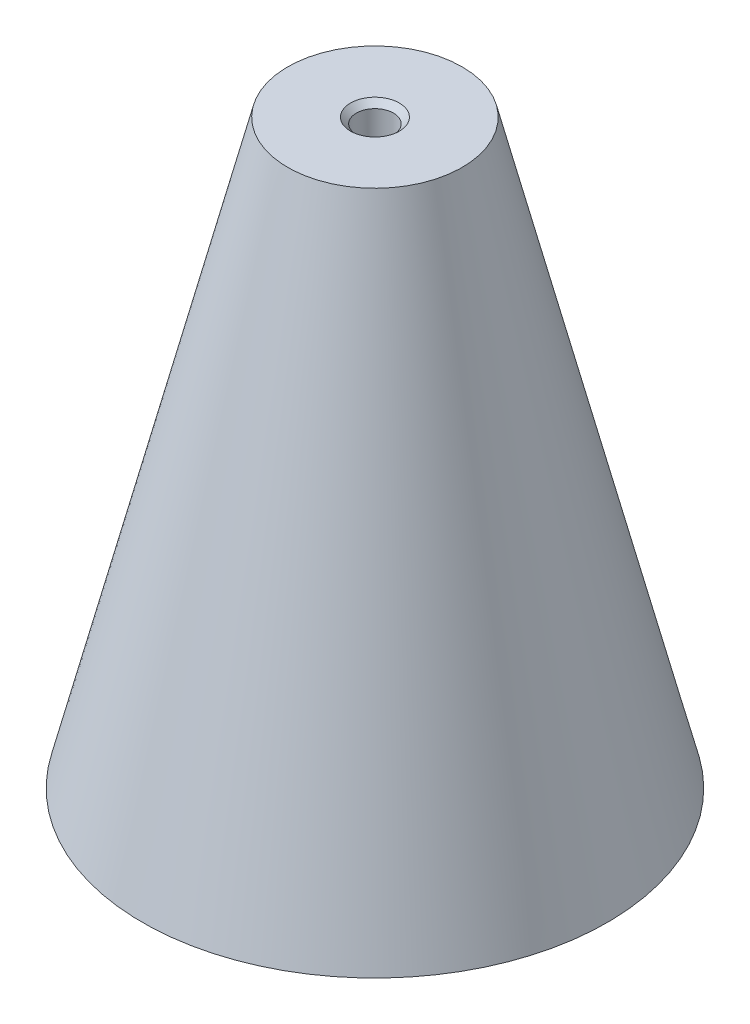
SolidWorks part; units mm, degrees
ref_plane "前视基准面" through (0, 0, 0) normal (0, 0, 1) x (1, 0, 0)
ref_plane "上视基准面" through (0, 0, 0) normal (0, 1, 0) x (1, 0, 0)
ref_plane "右视基准面" through (0, 0, 0) normal (1, 0, 0) x (0, 0, -1)
other "Configuration Table"
sketch "草图3" plane through (0, 0, 0) normal (1, 0, 0) x (0, 0, -1)
  line L0 (-7.5, 0) -> (0, 0)
  line L1 (0, 0) -> (0, -4)
  line L2 (0, -4) -> (-4.5, -4)
  line L3 (-4.5, -4) -> (-16, -50)
  line L4 (-16, -50) -> (-20, -50)
  line L5 (-20, -50) -> (-7.5, 0)
  line L6 (0, 28.4507) -> (0, 37.5487) construction
  dimension "D1" = 4
  dimension "D2" = 4
  dimension "D3" = 50
  dimension "D4" = 7.5
  dimension "D5" = 20
revolve "旋转1" add sketch "草图3" angle 360 about L6
sketch "草图4" plane through (0, 0, 0) normal (0, 1, 0) x (1, 0, 0)
  circle A0 centre (0, 0) radius 1.6
  dimension "D1" = 3.2
extrude "切除-拉伸1" cut sketch "草图4" against normal blind 10 contours A0
chamfer "倒角1" distance 0.5 angle 45 2 edges at (0, -4, 1.6) (0, 0, 1.6)
